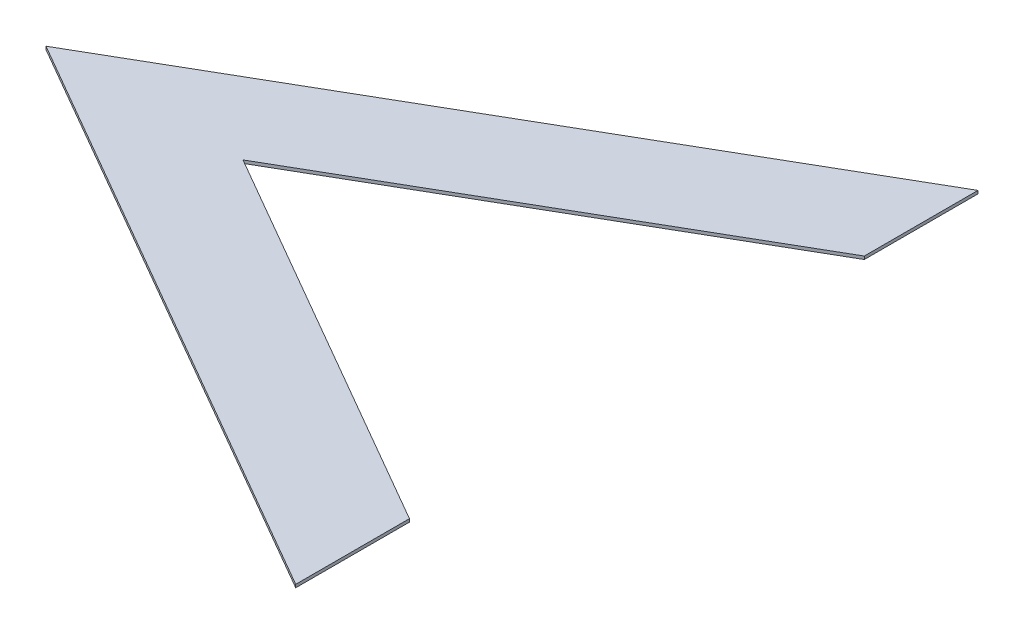
SolidWorks part; units mm, degrees
ref_plane "Front Plane" through (0, 0, 0) normal (0, 0, 1) x (1, 0, 0)
ref_plane "Top Plane" through (0, 0, 0) normal (0, 1, 0) x (1, 0, 0)
ref_plane "Right Plane" through (0, 0, 0) normal (1, 0, 0) x (0, 0, -1)
sketch "Sketch1" plane through (0, 71.1229, 0) normal (0, 1, 0) x (1, 0, 0)
  line L6 (34.5602, -76.2686) -> (-13.9372, -104.2686)
  line L7 (-13.9372, -104.2686) -> (34.5602, -132.2686)
  line L8 (34.5602, -132.2686) -> (34.5602, -122.9353)
  line L9 (34.5602, -122.9353) -> (2.2286, -104.2686)
  line L10 (2.2286, -104.2686) -> (34.5602, -85.602)
  line L11 (34.5602, -85.602) -> (34.5602, -76.2686)
  line L12 (34.5602, -76.2686) -> (-13.9372, -104.2686)
  line L13 (-13.9372, -104.2686) -> (34.5602, -132.2686)
  line L14 (34.5602, -132.2686) -> (34.5602, -122.9353)
  line L15 (34.5602, -122.9353) -> (2.2286, -104.2686)
  line L16 (2.2286, -104.2686) -> (34.5602, -85.602)
  line L17 (34.5602, -85.602) -> (34.5602, -76.2686)
  dimension "D1" = 0
extrude "Boss-Extrude1" add sketch "Sketch1" along normal blind 0.25
